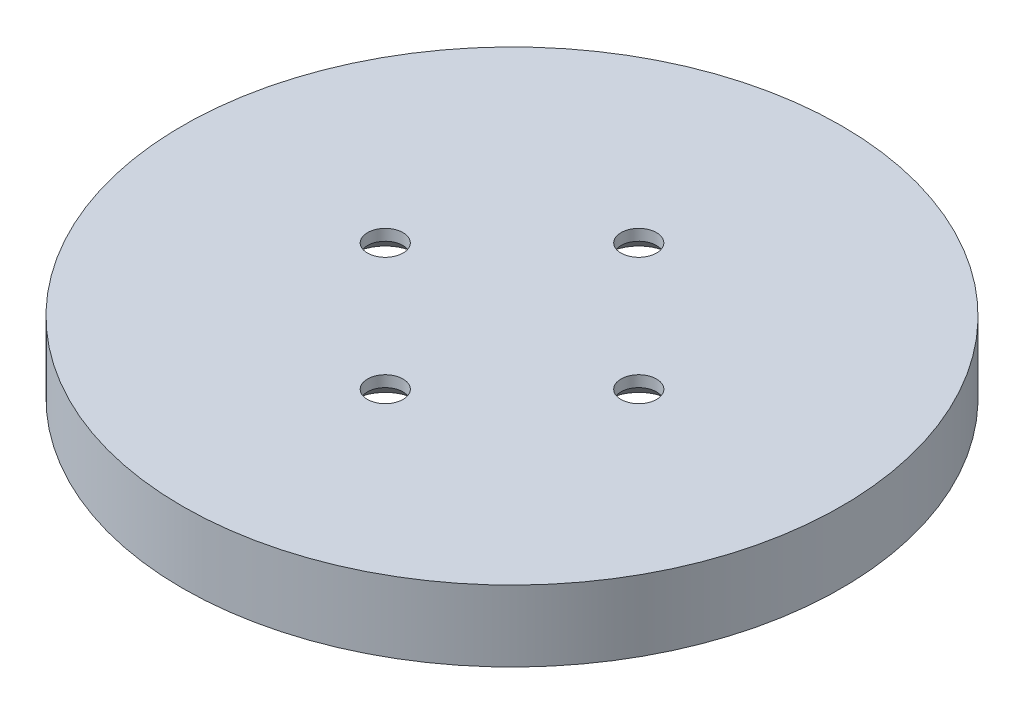
SolidWorks part; units mm, degrees
ref_plane "Front Plane" through (0, 0, 0) normal (0, 0, 1) x (1, 0, 0)
ref_plane "Top Plane" through (0, 0, 0) normal (0, 1, 0) x (1, 0, 0)
ref_plane "Right Plane" through (0, 0, 0) normal (1, 0, 0) x (0, 0, -1)
sketch "Sketch1" plane through (0, 0, 0) normal (0, 1, 0) x (1, 0, 0)
  circle A0 centre (0, 0) radius 65
  dimension "D1" = 130
extrude "Boss-Extrude2" add sketch "Sketch1" along normal blind 30
sketch "Sketch2" plane through (0, 30, 0) normal (0, 1, 0) x (1, 0, 0)
  circle A0 centre (0, 0) radius 52.6
  dimension "D1" = 105.2
extrude "Cut-Extrude1" cut sketch "Sketch2" against normal blind 84
sketch "Sketch4" plane through (0, 30, 0) normal (0, 1, 0) x (1, 0, 0)
  circle A0 centre (0, 0) radius 52.6
extrude "Boss-Extrude3" add sketch "Sketch4" against normal blind 5
sketch "Sketch5" plane through (0, 0, 0) normal (0, -1, 0) x (1, 0, 0)
  line L1 (-60.7, 4.6) -> (-44.5, 4.6)
  line L2 (-60.7, 4.6) -> (-60.7, -4.6)
  line L3 (-60.7, -4.6) -> (-44.5, -4.6)
  line L4 (-44.5, 4.6) -> (-44.5, -4.6)
  line L5 (-60.7, 4.6) -> (-44.5, -4.6) construction
  line L6 (-60.7, -4.6) -> (-44.5, 4.6) construction
  line L7 (44.5, 4.6) -> (60.7, 4.6)
  line L8 (44.5, 4.6) -> (44.5, -4.6)
  line L9 (44.5, -4.6) -> (60.7, -4.6)
  line L10 (60.7, 4.6) -> (60.7, -4.6)
  line L11 (44.5, 4.6) -> (60.7, -4.6) construction
  line L12 (44.5, -4.6) -> (60.7, 4.6) construction
  circle A0 centre (0, 0) radius 52.6 construction
  circle A1 centre (0, 0) radius 52.6 construction
  point P0 (-52.6, 0)
  point P9 (52.6, 0)
  dimension "D1" = 16.2
  dimension "D2" = 9.2
  dimension "D3" = 9.2
  dimension "D4" = 16.2
extrude "Cut-Extrude2" cut sketch "Sketch5" against normal blind 12
sketch "Sketch7" plane through (0, 12, 0) normal (0, -1, 0) x (1, 0, 0)
  line L0 (37.1938, -37.1938) -> (44.0703, -44.0703)
  line L1 (52.6, 0) -> (62.3248, 0)
  line L2 (-37.1938, 37.1938) -> (-44.0703, 44.0703)
  line L3 (-52.6, 0) -> (-62.3248, 0)
  arc A0 (-44.0703, 44.0703) -> (-62.3248, 0) centre (0, 0) ccw
  arc A1 (44.0703, -44.0703) -> (62.3248, 0) centre (0, 0) ccw
  arc A2 (37.1938, -37.1938) -> (52.6, 0) centre (0, 0) ccw
  arc A3 (-52.3985, -4.6) -> (52.3985, -4.6) centre (0, 0) ccw construction
  arc A4 (52.3985, -4.6) -> (52.3985, 4.6) centre (0, 0) ccw construction
  arc A5 (-37.1938, 37.1938) -> (-52.6, 0) centre (0, 0) ccw
  arc A6 (52.3985, 4.6) -> (-52.3985, 4.6) centre (0, 0) ccw construction
  arc A7 (-52.3985, 4.6) -> (-52.3985, -4.6) centre (0, 0) ccw construction
extrude "Cut-Extrude3" cut sketch "Sketch7" along normal blind 5.2
sketch "Sketch8" plane through (0, 30, 0) normal (0, 1, 0) x (1, 0, 0)
  circle A1 centre (0, 25) radius 3
  circle A2 centre (-25, 0) radius 3
  circle A3 centre (0, -25) radius 3
  circle A4 centre (25, 0) radius 3
  dimension "D2" = 6
  dimension "D3" = 6
  dimension "D4" = 6
  dimension "D5" = 6
hole_wizard "M6 Clearance Hole1" positions "3DSketch2" profile "Sketch9" hole size "M6" standard "ISO" end condition through all
sketch3d "3DSketch2"
  point P0 (0, 30, -25)
  point P3 (-25, 30, 0)
  point P6 (25, 30, 0)
  point P9 (0, 30, 25)
sketch "Sketch9" plane through (0, 30, -25) normal (1, 0, 0) x (0, 0, 1)
  line L0 (0, 0) -> (0, 30)
  line L1 (0, 30) -> (3.5, 30)
  line L2 (3.5, 30) -> (3.5, 0)
  line L5 (3.5, 0) -> (0, 0)
  line L11 (0, -6.35) -> (0, 107.95) construction
  dimension "Thru Hole Dia." = 7
  dimension "Thru Hole Depth" = 30
sketch "Sketch11" plane through (0, 30, 0) normal (0, 1, 0) x (1, 0, 0)
  circle A0 centre (0, 0) radius 65
extrude "Cut-Extrude4" cut sketch "Sketch11" against normal blind 18
sketch "Sketch12" plane through (0, 12, 0) normal (0, 1, 0) x (1, 0, 0)
  circle A0 centre (0, 0) radius 65
extrude "Boss-Extrude4" add sketch "Sketch12" along normal blind 5
sketch "Sketch20" plane through (0, 12, 0) normal (0, -1, 0) x (1, 0, 0)
  point P0 (0, 25)
  point P1 (-25, 0)
  point P3 (0, -25)
  point P5 (25, 0)
  point P7 (-175.8245, 85.8392)
hole_wizard "CSK for M6 Countersunk Flat Head Screw3" positions "3DSketch9" profile "Sketch21" countersink size "M6" standard "ISO" end condition through all
sketch3d "3DSketch9"
  point P0 (0, 30, 25)
  point P3 (-25, 30, 0)
  point P6 (-25, 12, 0)
  point P9 (0, 12, 25)
  point P12 (0, 12, -25)
  point P15 (25, 12, 0)
sketch "Sketch21" plane through (25, 12, 0) normal (1, 0, 0) x (0, 0, -1)
  line L0 (0, 0) -> (0, 5)
  line L1 (0, 5) -> (3.5, 5)
  line L2 (3.5, 5) -> (3.5, 2.8)
  line L3 (3.5, 2.8) -> (6.3, 0)
  line L5 (6.3, 0) -> (0, 0)
  line L6 (-3.5, 2.8) -> (-6.3, 0) construction
  line L11 (0, -6.35) -> (0, 107.95) construction
  dimension "Thru Hole Dia." = 7
  dimension "Thru Hole Depth" = 5
  dimension "Near C'Sink Dia." = 12.6
  dimension "Near C'Sink Angle" = 90
sketch "Sketch22" plane through (0, 0, 0) normal (0, -1, 0) x (1, 0, 0)
  line L0 (60.7, 4.6) -> (52.3985, 4.6) construction
  line L1 (60.7, -4.6) -> (52.3985, -4.6) construction
  line L2 (-52.3985, 4.6) -> (-60.7, 4.6)
  line L3 (-60.7, 4.6) -> (-60.7, -4.6)
  line L4 (-60.7, -4.6) -> (-52.3985, -4.6)
  line L5 (52.3985, 4.6) -> (60.7, 4.6)
  line L6 (60.7, 4.6) -> (60.7, -4.6)
  line L7 (60.7, -4.6) -> (52.3985, -4.6)
  circle A0 centre (0, 0) radius 65
  arc A1 (-52.3985, 4.6) -> (52.3985, 4.6) centre (0, 0) cw
  arc A2 (-52.3985, -4.6) -> (52.3985, -4.6) centre (0, 0) ccw
extrude "Cut-Extrude5" cut sketch "Sketch22" against normal blind 3
